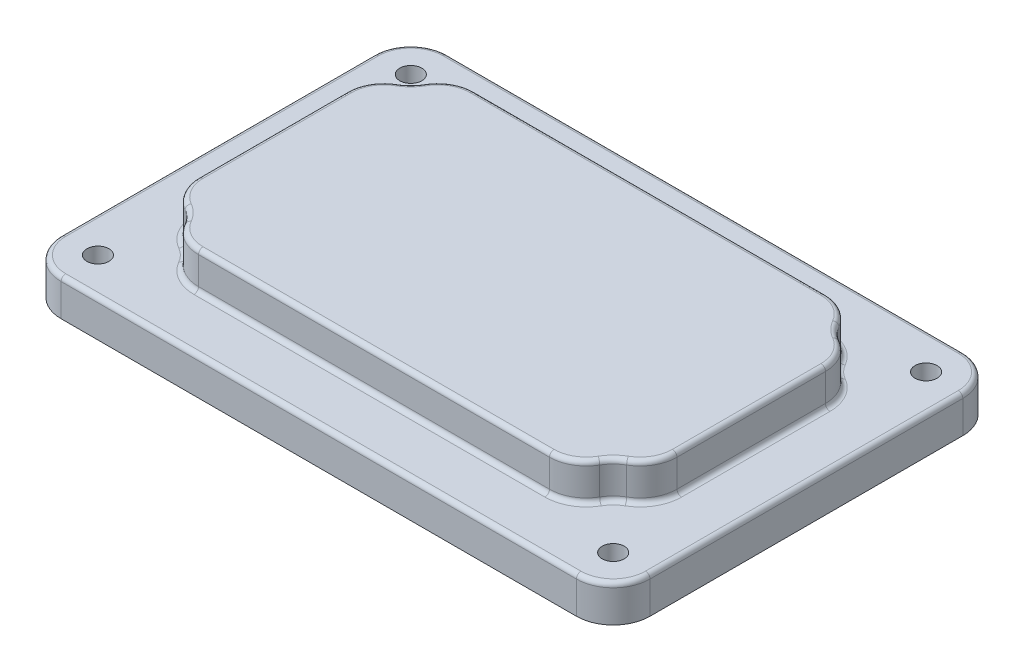
SolidWorks part; units mm, degrees
material "Cast Alloy Steel"
ref_plane "Front Plane" through (0, 0, 0) normal (0, 0, 1) x (1, 0, 0)
ref_plane "Top Plane" through (0, 0, 0) normal (0, 1, 0) x (1, 0, 0)
ref_plane "Right Plane" through (0, 0, 0) normal (1, 0, 0) x (0, 0, -1)
sketch "Sketch3" plane through (0, 0, 0) normal (0, 1, 0) x (1, 0, 0)
  line L1 (-44.45, -33.3375) -> (44.45, -33.3375)
  line L2 (-50.8, -26.9875) -> (-50.8, 26.9875)
  line L3 (-44.45, 33.3375) -> (44.45, 33.3375)
  line L4 (50.8, -26.9875) -> (50.8, 26.9875)
  line L5 (-50.8, -33.3375) -> (50.8, 33.3375) construction
  line L6 (-50.8, 33.3375) -> (50.8, -33.3375) construction
  arc A0 (44.45, -33.3375) -> (50.8, -26.9875) centre (44.45, -26.9875) ccw
  arc A1 (-44.45, -33.3375) -> (-50.8, -26.9875) centre (-44.45, -26.9875) cw
  arc A2 (-50.8, 26.9875) -> (-44.45, 33.3375) centre (-44.45, 26.9875) cw
  arc A3 (44.45, 33.3375) -> (50.8, 26.9875) centre (44.45, 26.9875) cw
  point P0 (0, 0)
  dimension "D1" = 6.35
extrude "Boss-Extrude1" add sketch "Sketch3" along normal blind 6.35
sketch "Sketch4" plane through (0, 6.35, 0) normal (0, 1, 0) x (1, 0, 0)
  line L12 (41.275, -23.8125) -> (41.275, 23.8125)
  line L13 (41.275, 23.8125) -> (-41.275, 23.8125)
  line L14 (-41.275, 23.8125) -> (-41.275, -23.8125)
  line L15 (-41.275, -23.8125) -> (41.275, -23.8125)
  line L16 (41.275, -23.8125) -> (41.275, 23.8125)
  line L17 (41.275, 23.8125) -> (-41.275, 23.8125)
  line L18 (-41.275, 23.8125) -> (-41.275, -23.8125)
  line L19 (-41.275, -23.8125) -> (41.275, -23.8125)
  dimension "D1" = 9.525
extrude "Boss-Extrude2" add sketch "Sketch4" along normal blind 6.35
sketch "Sketch5" plane through (0, 12.7, 0) normal (0, 1, 0) x (1, 0, 0)
  circle A0 centre (41.275, 23.8125) radius 6.35
  circle A1 centre (-41.275, 23.8125) radius 6.35
  circle A2 centre (-41.275, -23.8125) radius 6.35
  circle A3 centre (41.275, -23.8125) radius 6.35
  dimension "D1" = 12.7
  dimension "D2" = 12.7
  dimension "D3" = 12.7
  dimension "D4" = 12.7
extrude "Cut-Extrude1" cut sketch "Sketch5" against normal up to surface (6.35 mm away) up to face at (0, 6.35, 0)
fillet "Fillet1" radius 6.35 8 edges at (41.275, 9.525, -17.4625) (34.925, 9.525, -23.8125) (-34.925, 9.525, -23.8125) (-41.275, 9.525, -17.4625) (-41.275, 9.525, 17.4625) (34.925, 9.525, 23.8125) (41.275, 9.525, 17.4625) (-34.925, 9.525, 23.8125)
shell "Shell1" thickness 3.175
sketch "Sketch6" plane through (0, 0, 0) normal (0, -1, 0) x (1, 0, 0)
  circle A0 centre (-44.45, 26.9875) radius 6.35
  circle A1 centre (-44.45, -26.9875) radius 6.35
  circle A2 centre (44.45, -26.9875) radius 6.35
  circle A3 centre (44.45, 26.9875) radius 6.35
  arc A5 (-50.8, -26.9875) -> (-44.45, -33.3375) centre (-44.45, -26.9875) ccw construction
extrude "Boss-Extrude3" add sketch "Sketch6" against normal up to surface (3.175 mm away)
fillet "Fillet2" radius 0.7874 40 edges at (0, 6.35, 33.3375) (-48.9401, 6.35, 31.4776) (-50.8, 6.35, 0) (-48.9401, 6.35, -31.4776) (0, 6.35, -33.3375) (48.9401, 6.35, -31.4776) (50.8, 6.35, 0) (48.9401, 6.35, 31.4776) (40.4243, 6.35, -15.989) (36.7849, 12.7, -19.3224) (36.7849, 6.35, -19.3224) (33.4515, 6.35, -22.9618) (0, 6.35, -23.8125) (-33.4515, 6.35, -22.9618) (-36.7849, 12.7, -19.3224) (-36.7849, 6.35, -19.3224) (-40.4243, 6.35, -15.989) (-41.275, 6.35, 0) (-40.4243, 6.35, 15.989) (-36.7849, 12.7, 19.3224) (-36.7849, 6.35, 19.3224) (-33.4515, 6.35, 22.9618) (0, 6.35, 23.8125) (33.4515, 6.35, 22.9618) (36.7849, 12.7, 19.3224) (36.7849, 6.35, 19.3224) (40.4243, 6.35, 15.989) (41.275, 6.35, 0) (40.4243, 12.7, 15.989) (33.4515, 12.7, 22.9618) (0, 12.7, 23.8125) (-33.4515, 12.7, 22.9618) (-40.4243, 12.7, 15.989) (-41.275, 12.7, 0) (-40.4243, 12.7, -15.989) (-33.4515, 12.7, -22.9618) (0, 12.7, -23.8125) (33.4515, 12.7, -22.9618) (40.4243, 12.7, -15.989) (41.275, 12.7, 0)
fillet "Fillet3" radius 0.7874 56 edges at (39.9599, 0, -22.4974) (39.9599, 3.175, -22.4974) (-39.9599, 0, -22.4974) (-39.9599, 3.175, -22.4974) (-39.9599, 0, 22.4974) (-39.9599, 3.175, 22.4974) (39.9599, 3.175, 22.4974) (39.9599, 0, 22.4974) (47.625, 0, 0) (47.625, 1.5875, -21.4882) (47.625, 1.5875, 21.4882) (0, 0, -30.1625) (-38.9507, 1.5875, -30.1625) (38.9507, 1.5875, -30.1625) (-47.625, 0, 0) (-47.625, 1.5875, 21.4882) (-47.625, 1.5875, -21.4882) (-38.9507, 1.5875, 30.1625) (0, 0, 30.1625) (38.9507, 1.5875, 30.1625) (0, 3.175, -30.1625) (-47.625, 3.175, 0) (0, 3.175, 30.1625) (47.625, 3.175, 0) (0, 3.175, 20.6375) (0, 9.525, 20.6375) (38.1, 3.175, 0) (38.1, 9.525, 0) (0, 9.525, -20.6375) (0, 3.175, -20.6375) (-38.1, 9.525, 0) (-38.1, 3.175, 0) (34.5398, 9.525, -17.0773) (34.5398, 3.175, -17.0773) (-34.5398, 9.525, -17.0773) (-34.5398, 3.175, -17.0773) (-34.5398, 9.525, 17.0773) (-34.5398, 3.175, 17.0773) (34.5398, 9.525, 17.0773) (34.5398, 3.175, 17.0773) (37.6746, 9.525, -14.4015) (37.6746, 3.175, -14.4015) (31.864, 9.525, -20.2121) (31.864, 3.175, -20.2121) (-31.864, 9.525, -20.2121) (-31.864, 3.175, -20.2121) (-37.6746, 9.525, -14.4015) (-37.6746, 3.175, -14.4015) (-37.6746, 9.525, 14.4015) (-37.6746, 3.175, 14.4015) (31.864, 9.525, 20.2121) (31.864, 3.175, 20.2121) (37.6746, 9.525, 14.4015) (37.6746, 3.175, 14.4015) (-31.864, 9.525, 20.2121) (-31.864, 3.175, 20.2121)
hole_wizard "#6 Clearance Hole1" positions "Sketch7" profile "Sketch8" hole size "#6" standard "ANSI Inch" end condition through all
sketch "Sketch7" plane through (0, 0, 0) normal (0, -1, 0) x (-1, 0, 0)
  point P0 (-44.45, 26.9875)
  point P3 (44.45, 26.9875)
  point P6 (44.45, -26.9875)
  point P9 (-44.45, -26.9875)
sketch "Sketch8" plane through (44.45, 0, -26.9875) normal (1, 0, 0) x (0, 0, -1)
  line L0 (0, 0) -> (0, 12.7)
  line L1 (0, 12.7) -> (1.8986, 12.7)
  line L2 (1.8986, 12.7) -> (1.8986, 0)
  line L5 (1.8986, 0) -> (0, 0)
  line L11 (0, -6.35) -> (0, 107.95) construction
  dimension "Thru Hole Dia." = 3.7973
  dimension "Thru Hole Depth" = 12.7
